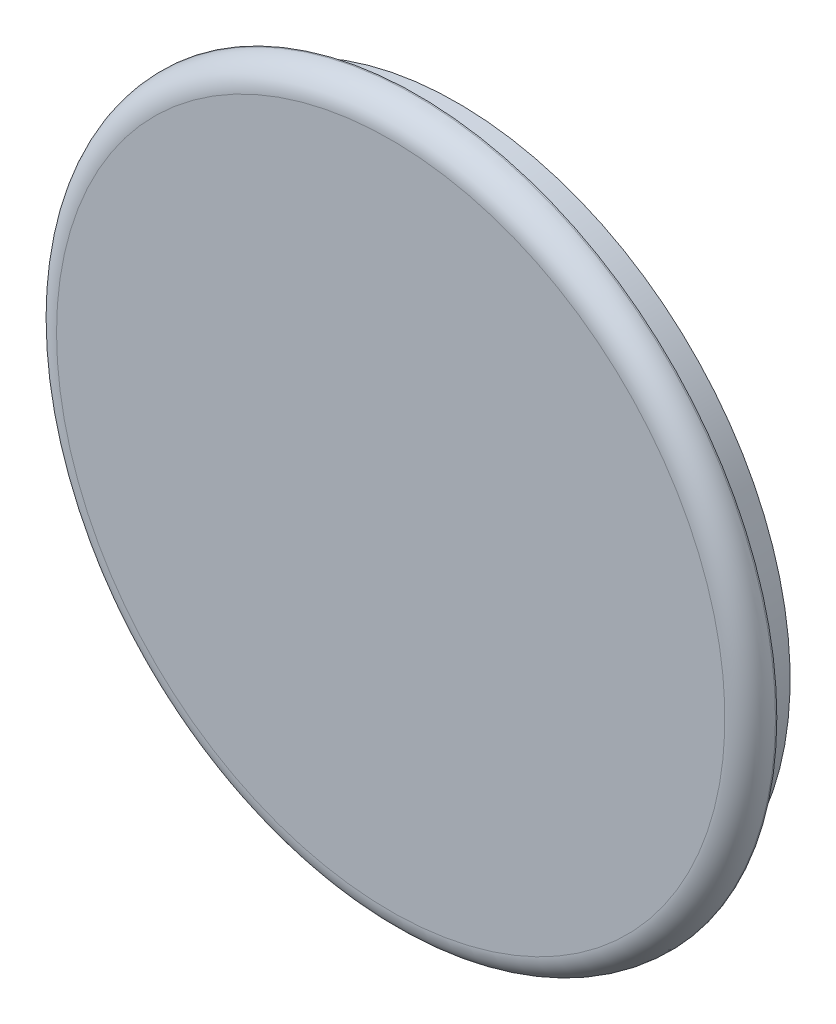
SolidWorks part; units mm, degrees
ref_plane "Front Plane" through (0, 0, 0) normal (0, 0, 1) x (1, 0, 0)
ref_plane "Top Plane" through (0, 0, 0) normal (0, 1, 0) x (1, 0, 0)
ref_plane "Right Plane" through (0, 0, 0) normal (1, 0, 0) x (0, 0, -1)
sketch "Sketch2" plane through (0, 0, 0) normal (0, 1, 0) x (1, 0, 0)
  line L0 (0, 0) -> (25.1, 0)
  line L1 (27, 1.9) -> (27, 2)
  line L2 (27, 2) -> (25, 2)
  line L3 (25, 2) -> (25, 5)
  line L4 (25, 5) -> (23, 5)
  line L5 (23, 5) -> (23, 2)
  line L6 (23, 2) -> (0, 2)
  line L7 (0, 2) -> (0, 0)
  arc A0 (25.1, 0) -> (27, 1.9) centre (25.1, 1.9) ccw
  point P11 (27, 0)
  dimension "D6" = 1.9
  dimension "D1" = 27
  dimension "D2" = 25
  dimension "D3" = 2
  dimension "D4" = 3
  dimension "D5" = 2
revolve "Revolve1" add sketch "Sketch2" angle 360 about L7
